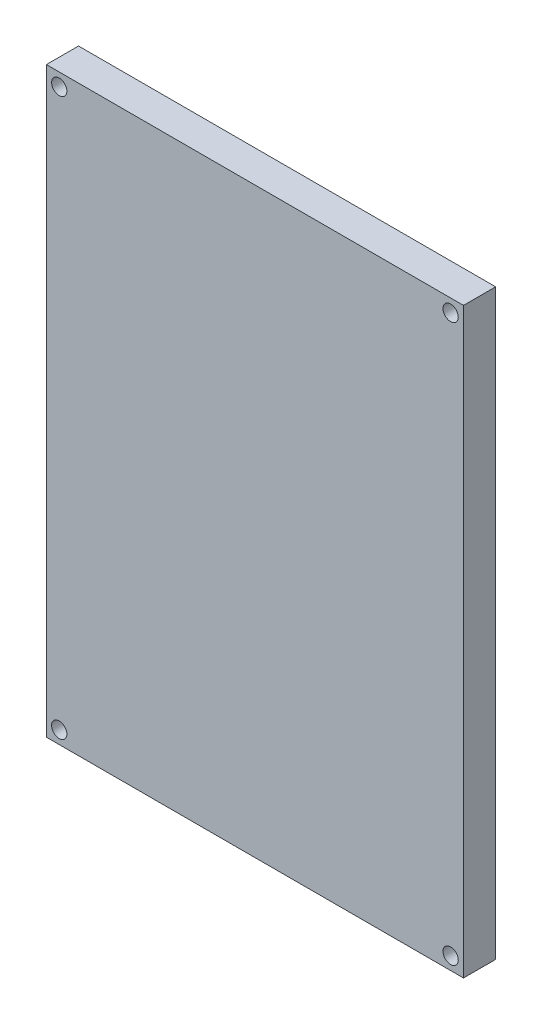
SolidWorks part; units mm, degrees
material "6061 合金"
ref_plane "前视基准面" through (0, 0, 0) normal (0, 0, 1) x (1, 0, 0)
ref_plane "上视基准面" through (0, 0, 0) normal (0, 1, 0) x (1, 0, 0)
ref_plane "右视基准面" through (0, 0, 0) normal (1, 0, 0) x (0, 0, -1)
other "Configuration Table"
sketch "草图1" plane through (0, 0, 0) normal (0, 0, 1) x (1, 0, 0)
  line L1 (0, 0) -> (25.95, 0)
  line L2 (0, 0) -> (0, 36.24)
  line L3 (0, 36.24) -> (25.95, 36.24)
  line L4 (25.95, 0) -> (25.95, 36.24)
  dimension "D1" = 25.95
  dimension "D2" = 36.24
extrude "凸台-拉伸1" add sketch "草图1" along normal blind 2
sketch "草图2" plane through (0, 0, 2) normal (0, 0, 1) x (1, 0, 0)
  line L0 (12.1036, 3.2831) -> (12.1036, 33.1973) construction
  text T0 "信通学院CRFICS\r\n48MHz 1分4时钟信号源" font "宋体" height 3
hole_wizard "M1.2x0.25 螺纹孔1" positions "3D草图2" profile "草图4" tap size "M1.2x0.25" standard "GB" end condition through all
sketch3d "3D草图2"
  point P0 (0.8, 0.8, 2)
  point P2 (25.15, 0.8, 2)
  point P4 (25.15, 35.44, 2)
  point P6 (0.8, 35.44, 2)
sketch "草图4" plane through (0.8, 0.8, 2) normal (1, 0, 0) x (0, -1, 0)
  line L0 (0, 0) -> (0, 2)
  line L1 (0, 2) -> (0.475, 2)
  line L2 (0.475, 2) -> (0.475, 0)
  line L5 (0.475, 0) -> (0, 0)
  line L11 (0, -6.35) -> (0, 107.95) construction
  dimension "通孔螺纹孔钻头直径" = 0.95
  dimension "通孔螺纹孔钻头深度" = 2
cosmetic thread "孔螺纹线1" parameters "D2"=1.2
cosmetic thread "孔螺纹线2" parameters "D2"=1.2
cosmetic thread "孔螺纹线3" parameters "D2"=1.2
cosmetic thread "孔螺纹线4" parameters "D2"=1.2
